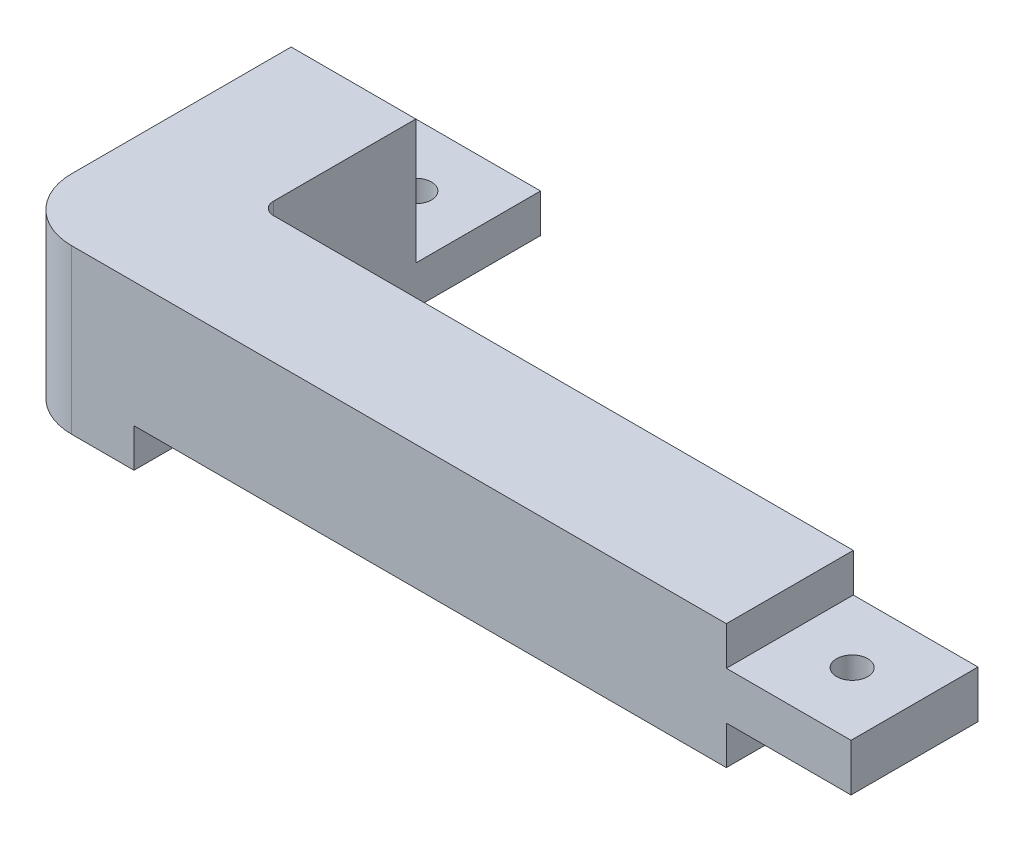
SolidWorks part; units mm, degrees
ref_plane "Front Plane" through (0, 0, 0) normal (0, 0, 1) x (1, 0, 0)
ref_plane "Top Plane" through (0, 0, 0) normal (0, 1, 0) x (1, 0, 0)
ref_plane "Right Plane" through (0, 0, 0) normal (1, 0, 0) x (0, 0, -1)
sketch "Sketch1" plane through (0, 0, 0) normal (0, 1, 0) x (1, 0, 0)
  line L1 (26.3502, -56.9444) -> (0.9502, -56.9444)
  line L2 (26.3502, -56.9444) -> (26.3502, 25.8596)
  line L3 (26.3502, 25.8596) -> (0.9502, 25.8596)
  line L4 (0.9502, -56.9444) -> (0.9502, 25.8596)
  dimension "D1" = 82.804
  dimension "D2" = 25.4
extrude "Boss-Extrude1" add sketch "Sketch1" along normal blind 33.274
sketch "Sketch3" plane through (26.3502, 0, 0) normal (1, 0, 0) x (0, 0, -1)
  line L1 (-31.0847, 33.274) -> (-56.9444, 33.274)
  line L2 (-31.0847, 33.274) -> (-31.0847, 7.874)
  line L3 (-31.0847, 7.874) -> (-56.9444, 7.874)
  line L4 (-56.9444, 33.274) -> (-56.9444, 7.874)
  point P5 (0, 0)
  dimension "D1" = 25.4
extrude "Boss-Extrude2" add sketch "Sketch3" along normal blind 120.65
sketch "Sketch8" plane through (0, 0, -25.8596) normal (0, 0, -1) x (-1, 0, 0)
  line L0 (-0.9502, 33.274) -> (-0.9502, 0) construction
  line L1 (-26.3502, 33.274) -> (-0.9502, 33.274)
  line L2 (-26.3502, 33.274) -> (-26.3502, 7.874)
  line L3 (-26.3502, 7.874) -> (-0.9502, 7.874)
  line L4 (-0.9502, 33.274) -> (-0.9502, 7.874)
  dimension "D1" = 25.4
extrude "Cut-Extrude5" cut sketch "Sketch8" against normal blind 25.4
sketch "Sketch5" plane through (147.0002, 0, 0) normal (1, 0, 0) x (0, 0, -1)
  line L0 (-56.9444, 15.748) -> (-31.0847, 15.748)
  line L1 (-56.9444, 33.274) -> (-56.9444, 7.874) construction
  line L2 (-31.0847, 7.874) -> (-31.0847, 33.274) construction
  line L3 (-56.9444, 25.4) -> (-31.0847, 25.4)
  line L4 (-31.0847, 33.274) -> (-56.9444, 33.274) construction
  line L5 (-56.9444, 25.4) -> (-56.9444, 15.748)
  line L6 (-31.0847, 25.4) -> (-31.0847, 15.748)
  dimension "D1" = 7.874
  dimension "D2" = 9.652
extrude "Boss-Extrude3" add sketch "Sketch5" along normal blind 25.4
sketch "Sketch7" plane through (0, 25.4, 0) normal (0, 1, 0) x (1, 0, 0)
  line L0 (147.0002, -31.0847) -> (172.4002, -56.9444) construction
  circle A0 centre (159.7002, -44.0145) radius 3.175
  point P8 (0, 0)
  point P9 (159.7002, -44.0145)
  dimension "D1" = 6.35
extrude "Cut-Extrude4" cut sketch "Sketch7" against normal blind 41.402
fillet "Fillet1" radius 12.7 1 edges at (0.9502, 16.637, 56.9444)
fillet "Fillet2" radius 2.54 1 edges at (26.3502, 20.574, 31.0847)
sketch "Sketch9" plane through (0, 7.874, 0) normal (0, 1, 0) x (1, 0, 0)
  line L0 (0.9502, 25.8596) -> (26.3502, 0.4596) construction
  circle A0 centre (13.6502, 13.1596) radius 3.175
  dimension "D1" = 6.35
extrude "Cut-Extrude6" cut sketch "Sketch9" against normal blind 25.4
